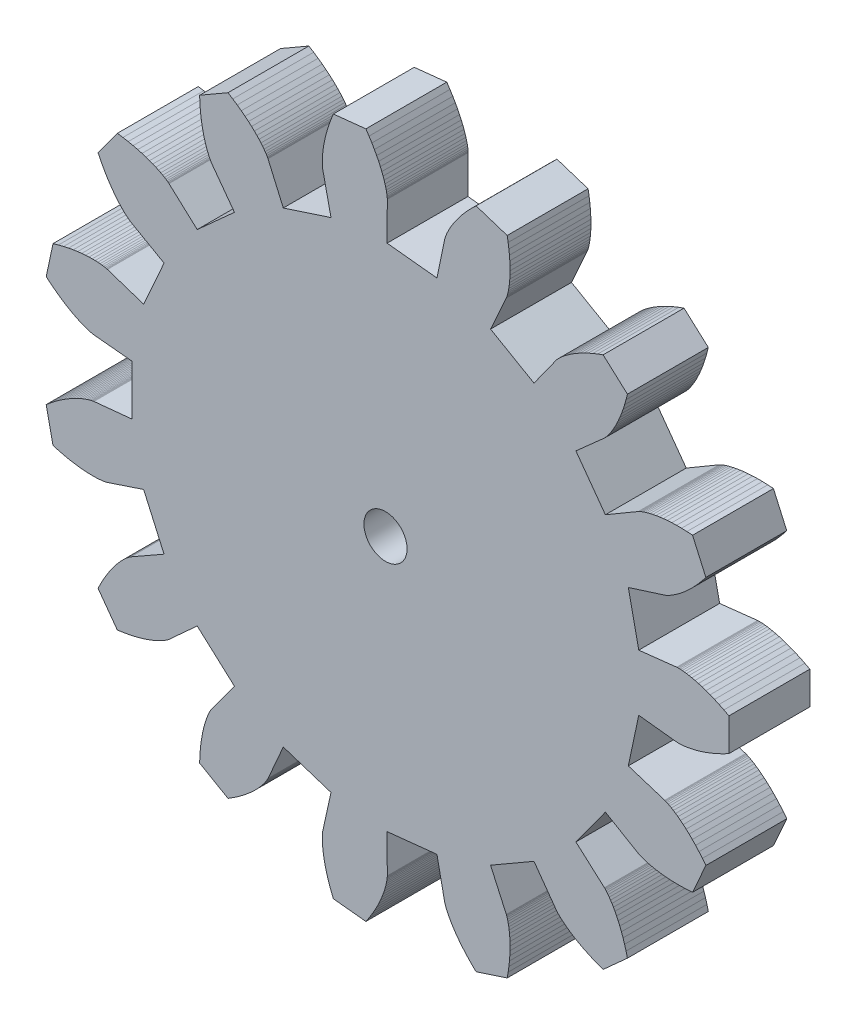
SolidWorks part; units mm, degrees
material "Acrylic (Medium-high impact)"
ref_plane "Front Plane" through (0, 0, 0) normal (0, 0, 1) x (1, 0, 0)
ref_plane "Top Plane" through (0, 0, 0) normal (0, 1, 0) x (1, 0, 0)
ref_plane "Right Plane" through (0, 0, 0) normal (1, 0, 0) x (0, 0, -1)
sketch "Model" plane through (0, 0, 0) normal (0, 0, 1) x (1, 0, 0)
  line L0 (18.784, 2.0911) -> (21.5999, 2.4046)
  line L1 (21.5999, 2.4046) -> (21.6112, 2.4056)
  line L2 (21.6112, 2.4056) -> (21.6451, 2.4077)
  line L3 (21.6451, 2.4077) -> (21.7018, 2.4093)
  line L4 (21.7018, 2.4093) -> (21.7812, 2.4091)
  line L5 (21.7812, 2.4091) -> (21.8831, 2.4055)
  line L6 (21.8831, 2.4055) -> (22.0076, 2.3971)
  line L7 (22.0076, 2.3971) -> (22.1542, 2.3825)
  line L8 (22.1542, 2.3825) -> (22.3228, 2.3602)
  line L9 (22.3228, 2.3602) -> (22.513, 2.3287)
  line L10 (22.513, 2.3287) -> (22.7243, 2.2867)
  line L11 (22.7243, 2.2867) -> (22.9562, 2.2327)
  line L12 (22.9562, 2.2327) -> (23.2081, 2.1655)
  line L13 (23.2081, 2.1655) -> (23.4794, 2.0836)
  line L14 (23.4794, 2.0836) -> (23.7695, 1.9857)
  line L15 (23.7695, 1.9857) -> (24.0775, 1.8706)
  line L16 (24.0775, 1.8706) -> (24.4026, 1.737)
  line L17 (24.4026, 1.737) -> (24.7438, 1.5837)
  line L18 (24.7438, 1.5837) -> (25.1004, 1.4094)
  line L19 (25.1004, 1.4094) -> (25.4711, 1.2132)
  line L20 (25.4711, 1.2132) -> (25.4711, -1.2132)
  line L21 (25.4711, -1.2132) -> (25.1004, -1.4094)
  line L22 (25.1004, -1.4094) -> (24.7438, -1.5837)
  line L23 (24.7438, -1.5837) -> (24.4026, -1.737)
  line L24 (24.4026, -1.737) -> (24.0775, -1.8706)
  line L25 (24.0775, -1.8706) -> (23.7695, -1.9857)
  line L26 (23.7695, -1.9857) -> (23.4794, -2.0836)
  line L27 (23.4794, -2.0836) -> (23.2081, -2.1655)
  line L28 (23.2081, -2.1655) -> (22.9562, -2.2327)
  line L29 (22.9562, -2.2327) -> (22.7243, -2.2867)
  line L30 (22.7243, -2.2867) -> (22.513, -2.3287)
  line L31 (22.513, -2.3287) -> (22.3228, -2.3602)
  line L32 (22.3228, -2.3602) -> (22.1542, -2.3825)
  line L33 (22.1542, -2.3825) -> (22.0076, -2.3971)
  line L34 (22.0076, -2.3971) -> (21.8831, -2.4055)
  line L35 (21.8831, -2.4055) -> (21.7812, -2.4091)
  line L36 (21.7812, -2.4091) -> (21.7018, -2.4093)
  line L37 (21.7018, -2.4093) -> (21.6451, -2.4077)
  line L38 (21.6451, -2.4077) -> (21.6112, -2.4056)
  line L39 (21.6112, -2.4056) -> (21.5999, -2.4046)
  line L40 (21.5999, -2.4046) -> (18.784, -2.0911)
  line L41 (18.784, -2.0911) -> (18.0105, -5.7298)
  line L42 (18.0105, -5.7298) -> (20.7105, -6.5887)
  line L43 (20.7105, -6.5887) -> (20.7213, -6.5924)
  line L44 (20.7213, -6.5924) -> (20.7531, -6.6043)
  line L45 (20.7531, -6.6043) -> (20.8056, -6.6259)
  line L46 (20.8056, -6.6259) -> (20.878, -6.6584)
  line L47 (20.878, -6.6584) -> (20.9697, -6.7031)
  line L48 (20.9697, -6.7031) -> (21.0799, -6.7614)
  line L49 (21.0799, -6.7614) -> (21.2079, -6.8344)
  line L50 (21.2079, -6.8344) -> (21.3529, -6.9234)
  line L51 (21.3529, -6.9234) -> (21.5138, -7.0295)
  line L52 (21.5138, -7.0295) -> (21.6897, -7.1538)
  line L53 (21.6897, -7.1538) -> (21.8796, -7.2974)
  line L54 (21.8796, -7.2974) -> (22.0824, -7.4613)
  line L55 (22.0824, -7.4613) -> (22.297, -7.6465)
  line L56 (22.297, -7.6465) -> (22.5222, -7.8539)
  line L57 (22.5222, -7.8539) -> (22.7567, -8.0843)
  line L58 (22.7567, -8.0843) -> (22.9993, -8.3386)
  line L59 (22.9993, -8.3386) -> (23.2488, -8.6175)
  line L60 (23.2488, -8.6175) -> (23.5036, -8.9216)
  line L61 (23.5036, -8.9216) -> (23.7625, -9.2517)
  line L62 (23.7625, -9.2517) -> (22.7756, -11.4683)
  line L63 (22.7756, -11.4683) -> (22.357, -11.4968)
  line L64 (22.357, -11.4968) -> (21.9605, -11.511)
  line L65 (21.9605, -11.511) -> (21.5863, -11.5123)
  line L66 (21.5863, -11.5123) -> (21.235, -11.5021)
  line L67 (21.235, -11.5021) -> (20.9068, -11.482)
  line L68 (20.9068, -11.482) -> (20.6021, -11.4534)
  line L69 (20.6021, -11.4534) -> (20.3209, -11.4179)
  line L70 (20.3209, -11.4179) -> (20.0633, -11.3768)
  line L71 (20.0633, -11.3768) -> (19.8296, -11.3318)
  line L72 (19.8296, -11.3318) -> (19.6195, -11.2842)
  line L73 (19.6195, -11.2842) -> (19.4329, -11.2356)
  line L74 (19.4329, -11.2356) -> (19.2698, -11.1875)
  line L75 (19.2698, -11.1875) -> (19.1299, -11.1412)
  line L76 (19.1299, -11.1412) -> (19.0128, -11.0982)
  line L77 (19.0128, -11.0982) -> (18.9182, -11.06)
  line L78 (18.9182, -11.06) -> (18.8456, -11.028)
  line L79 (18.8456, -11.028) -> (18.7945, -11.0034)
  line L80 (18.7945, -11.0034) -> (18.7643, -10.9877)
  line L81 (18.7643, -10.9877) -> (18.7544, -10.9822)
  line L82 (18.7544, -10.9822) -> (16.3095, -9.5505)
  line L83 (16.3095, -9.5505) -> (14.1229, -12.56)
  line L84 (14.1229, -12.56) -> (16.2401, -14.4428)
  line L85 (16.2401, -14.4428) -> (16.2484, -14.4506)
  line L86 (16.2484, -14.4506) -> (16.2727, -14.4744)
  line L87 (16.2727, -14.4744) -> (16.3118, -14.5154)
  line L88 (16.3118, -14.5154) -> (16.3648, -14.5745)
  line L89 (16.3648, -14.5745) -> (16.4303, -14.6527)
  line L90 (16.4303, -14.6527) -> (16.5074, -14.7508)
  line L91 (16.5074, -14.7508) -> (16.5946, -14.8696)
  line L92 (16.5946, -14.8696) -> (16.6908, -15.0098)
  line L93 (16.6908, -15.0098) -> (16.7947, -15.1722)
  line L94 (16.7947, -15.1722) -> (16.9048, -15.3573)
  line L95 (16.9048, -15.3573) -> (17.0199, -15.5657)
  line L96 (17.0199, -15.5657) -> (17.1385, -15.798)
  line L97 (17.1385, -15.798) -> (17.2592, -16.0544)
  line L98 (17.2592, -16.0544) -> (17.3806, -16.3355)
  line L99 (17.3806, -16.3355) -> (17.5011, -16.6414)
  line L100 (17.5011, -16.6414) -> (17.6193, -16.9723)
  line L101 (17.6193, -16.9723) -> (17.7338, -17.3286)
  line L102 (17.7338, -17.3286) -> (17.8428, -17.7101)
  line L103 (17.8428, -17.7101) -> (17.9451, -18.1169)
  line L104 (17.9451, -18.1169) -> (16.1419, -19.7405)
  line L105 (16.1419, -19.7405) -> (15.748, -19.5963)
  line L106 (15.748, -19.5963) -> (15.38, -19.4479)
  line L107 (15.38, -19.4479) -> (15.0376, -19.2969)
  line L108 (15.0376, -19.2969) -> (14.7208, -19.1447)
  line L109 (14.7208, -19.1447) -> (14.4292, -18.9929)
  line L110 (14.4292, -18.9929) -> (14.1624, -18.8428)
  line L111 (14.1624, -18.8428) -> (13.92, -18.696)
  line L112 (13.92, -18.696) -> (13.7014, -18.5537)
  line L113 (13.7014, -18.5537) -> (13.5062, -18.4175)
  line L114 (13.5062, -18.4175) -> (13.3336, -18.2886)
  line L115 (13.3336, -18.2886) -> (13.1829, -18.1683)
  line L116 (13.1829, -18.1683) -> (13.0535, -18.058)
  line L117 (13.0535, -18.058) -> (12.9445, -17.9588)
  line L118 (12.9445, -17.9588) -> (12.855, -17.872)
  line L119 (12.855, -17.872) -> (12.7841, -17.7986)
  line L120 (12.7841, -17.7986) -> (12.7308, -17.7397)
  line L121 (12.7308, -17.7397) -> (12.6942, -17.6965)
  line L122 (12.6942, -17.6965) -> (12.673, -17.6699)
  line L123 (12.673, -17.6699) -> (12.6662, -17.6609)
  line L124 (12.6662, -17.6609) -> (11.0149, -15.3584)
  line L125 (11.0149, -15.3584) -> (7.7934, -17.2184)
  line L126 (7.7934, -17.2184) -> (8.9617, -19.7996)
  line L127 (8.9617, -19.7996) -> (8.9661, -19.8101)
  line L128 (8.9661, -19.8101) -> (8.9786, -19.8417)
  line L129 (8.9786, -19.8417) -> (8.9976, -19.8951)
  line L130 (8.9976, -19.8951) -> (9.022, -19.9707)
  line L131 (9.022, -19.9707) -> (9.0501, -20.0688)
  line L132 (9.0501, -20.0688) -> (9.0805, -20.1897)
  line L133 (9.0805, -20.1897) -> (9.1119, -20.3337)
  line L134 (9.1119, -20.3337) -> (9.1428, -20.5009)
  line L135 (9.1428, -20.5009) -> (9.1716, -20.6915)
  line L136 (9.1716, -20.6915) -> (9.1969, -20.9054)
  line L137 (9.1969, -20.9054) -> (9.2173, -21.1426)
  line L138 (9.2173, -21.1426) -> (9.2312, -21.403)
  line L139 (9.2312, -21.403) -> (9.2372, -21.6864)
  line L140 (9.2372, -21.6864) -> (9.2337, -21.9925)
  line L141 (9.2337, -21.9925) -> (9.2194, -22.321)
  line L142 (9.2194, -22.321) -> (9.1928, -22.6714)
  line L143 (9.1928, -22.6714) -> (9.1524, -23.0434)
  line L144 (9.1524, -23.0434) -> (9.0969, -23.4363)
  line L145 (9.0969, -23.4363) -> (9.0248, -23.8496)
  line L146 (9.0248, -23.8496) -> (6.7172, -24.5994)
  line L147 (6.7172, -24.5994) -> (6.416, -24.3074)
  line L148 (6.416, -24.3074) -> (6.1401, -24.0222)
  line L149 (6.1401, -24.0222) -> (5.8888, -23.745)
  line L150 (5.8888, -23.745) -> (5.6613, -23.4771)
  line L151 (5.6613, -23.4771) -> (5.4566, -23.2198)
  line L152 (5.4566, -23.2198) -> (5.2739, -22.9741)
  line L153 (5.2739, -22.9741) -> (5.1122, -22.7414)
  line L154 (5.1122, -22.7414) -> (4.9704, -22.5226)
  line L155 (4.9704, -22.5226) -> (4.8474, -22.3187)
  line L156 (4.8474, -22.3187) -> (4.7422, -22.1307)
  line L157 (4.7422, -22.1307) -> (4.6535, -21.9596)
  line L158 (4.6535, -21.9596) -> (4.5801, -21.8062)
  line L159 (4.5801, -21.8062) -> (4.5209, -21.6712)
  line L160 (4.5209, -21.6712) -> (4.4745, -21.5555)
  line L161 (4.4745, -21.5555) -> (4.4395, -21.4596)
  line L162 (4.4395, -21.4596) -> (4.4148, -21.3842)
  line L163 (4.4148, -21.3842) -> (4.3989, -21.3298)
  line L164 (4.3989, -21.3298) -> (4.3903, -21.2968)
  line L165 (4.3903, -21.2968) -> (4.3878, -21.2858)
  line L166 (4.3878, -21.2858) -> (3.8158, -18.5108)
  line L167 (3.8158, -18.5108) -> (0.1162, -18.8996)
  line L168 (0.1162, -18.8996) -> (0.1337, -21.7329)
  line L169 (0.1337, -21.7329) -> (0.1335, -21.7443)
  line L170 (0.1335, -21.7443) -> (0.132, -21.7782)
  line L171 (0.132, -21.7782) -> (0.1277, -21.8348)
  line L172 (0.1277, -21.8348) -> (0.1192, -21.9137)
  line L173 (0.1192, -21.9137) -> (0.1049, -22.0147)
  line L174 (0.1049, -22.0147) -> (0.0836, -22.1376)
  line L175 (0.0836, -22.1376) -> (0.0537, -22.2819)
  line L176 (0.0537, -22.2819) -> (0.0139, -22.4472)
  line L177 (0.0139, -22.4472) -> (-0.0373, -22.6331)
  line L178 (-0.0373, -22.6331) -> (-0.1012, -22.8388)
  line L179 (-0.1012, -22.8388) -> (-0.1791, -23.0638)
  line L180 (-0.1791, -23.0638) -> (-0.2723, -23.3073)
  line L181 (-0.2723, -23.3073) -> (-0.3821, -23.5686)
  line L182 (-0.3821, -23.5686) -> (-0.5097, -23.8469)
  line L183 (-0.5097, -23.8469) -> (-0.6564, -24.1411)
  line L184 (-0.6564, -24.1411) -> (-0.8233, -24.4504)
  line L185 (-0.8233, -24.4504) -> (-1.0114, -24.7738)
  line L186 (-1.0114, -24.7738) -> (-1.222, -25.1102)
  line L187 (-1.222, -25.1102) -> (-1.4559, -25.4584)
  line L188 (-1.4559, -25.4584) -> (-3.869, -25.2048)
  line L189 (-3.869, -25.2048) -> (-4.0254, -24.8155)
  line L190 (-4.0254, -24.8155) -> (-4.1614, -24.4427)
  line L191 (-4.1614, -24.4427) -> (-4.2783, -24.0873)
  line L192 (-4.2783, -24.0873) -> (-4.3772, -23.75)
  line L193 (-4.3772, -23.75) -> (-4.4594, -23.4317)
  line L194 (-4.4594, -23.4317) -> (-4.5265, -23.133)
  line L195 (-4.5265, -23.133) -> (-4.5795, -22.8546)
  line L196 (-4.5795, -22.8546) -> (-4.6201, -22.597)
  line L197 (-4.6201, -22.597) -> (-4.6495, -22.3607)
  line L198 (-4.6495, -22.3607) -> (-4.6692, -22.1462)
  line L199 (-4.6692, -22.1462) -> (-4.6806, -21.9538)
  line L200 (-4.6806, -21.9538) -> (-4.6852, -21.7838)
  line L201 (-4.6852, -21.7838) -> (-4.6844, -21.6364)
  line L202 (-4.6844, -21.6364) -> (-4.6798, -21.5118)
  line L203 (-4.6798, -21.5118) -> (-4.6727, -21.41)
  line L204 (-4.6727, -21.41) -> (-4.6646, -21.3311)
  line L205 (-4.6646, -21.3311) -> (-4.657, -21.2749)
  line L206 (-4.657, -21.2749) -> (-4.6514, -21.2413)
  line L207 (-4.6514, -21.2413) -> (-4.6493, -21.2302)
  line L208 (-4.6493, -21.2302) -> (-4.0431, -18.4625)
  line L209 (-4.0431, -18.4625) -> (-7.581, -17.313)
  line L210 (-7.581, -17.313) -> (-8.7175, -19.9084)
  line L211 (-8.7175, -19.9084) -> (-8.7222, -19.9187)
  line L212 (-8.7222, -19.9187) -> (-8.7374, -19.9491)
  line L213 (-8.7374, -19.9491) -> (-8.7643, -19.999)
  line L214 (-8.7643, -19.999) -> (-8.8042, -20.0676)
  line L215 (-8.8042, -20.0676) -> (-8.8583, -20.1541)
  line L216 (-8.8583, -20.1541) -> (-8.9278, -20.2577)
  line L217 (-8.9278, -20.2577) -> (-9.0138, -20.3774)
  line L218 (-9.0138, -20.3774) -> (-9.1174, -20.5122)
  line L219 (-9.1174, -20.5122) -> (-9.2398, -20.6612)
  line L220 (-9.2398, -20.6612) -> (-9.3818, -20.8231)
  line L221 (-9.3818, -20.8231) -> (-9.5445, -20.997)
  line L222 (-9.5445, -20.997) -> (-9.7287, -21.1815)
  line L223 (-9.7287, -21.1815) -> (-9.9353, -21.3756)
  line L224 (-9.9353, -21.3756) -> (-10.165, -21.5779)
  line L225 (-10.165, -21.5779) -> (-10.4187, -21.787)
  line L226 (-10.4187, -21.787) -> (-10.697, -22.0017)
  line L227 (-10.697, -22.0017) -> (-11.0004, -22.2206)
  line L228 (-11.0004, -22.2206) -> (-11.3296, -22.4423)
  line L229 (-11.3296, -22.4423) -> (-11.6849, -22.6652)
  line L230 (-11.6849, -22.6652) -> (-13.7862, -21.452)
  line L231 (-13.7862, -21.452) -> (-13.7708, -21.0328)
  line L232 (-13.7708, -21.0328) -> (-13.7434, -20.6369)
  line L233 (-13.7434, -20.6369) -> (-13.7056, -20.2647)
  line L234 (-13.7056, -20.2647) -> (-13.6587, -19.9164)
  line L235 (-13.6587, -19.9164) -> (-13.6044, -19.5921)
  line L236 (-13.6044, -19.5921) -> (-13.5442, -19.292)
  line L237 (-13.5442, -19.292) -> (-13.4794, -19.0161)
  line L238 (-13.4794, -19.0161) -> (-13.4117, -18.7642)
  line L239 (-13.4117, -18.7642) -> (-13.3425, -18.5364)
  line L240 (-13.3425, -18.5364) -> (-13.2732, -18.3325)
  line L241 (-13.2732, -18.3325) -> (-13.2054, -18.152)
  line L242 (-13.2054, -18.152) -> (-13.1404, -17.9949)
  line L243 (-13.1404, -17.9949) -> (-13.0798, -17.8605)
  line L244 (-13.0798, -17.8605) -> (-13.0248, -17.7486)
  line L245 (-13.0248, -17.7486) -> (-12.9769, -17.6585)
  line L246 (-12.9769, -17.6585) -> (-12.9375, -17.5896)
  line L247 (-12.9375, -17.5896) -> (-12.9077, -17.5414)
  line L248 (-12.9077, -17.5414) -> (-12.8889, -17.513)
  line L249 (-12.8889, -17.513) -> (-12.8824, -17.5037)
  line L250 (-12.8824, -17.5037) -> (-11.203, -15.2218)
  line L251 (-11.203, -15.2218) -> (-13.9674, -12.7327)
  line L252 (-13.9674, -12.7327) -> (-16.0613, -14.6415)
  line L253 (-16.0613, -14.6415) -> (-16.0698, -14.6489)
  line L254 (-16.0698, -14.6489) -> (-16.0961, -14.6706)
  line L255 (-16.0961, -14.6706) -> (-16.1409, -14.7052)
  line L256 (-16.1409, -14.7052) -> (-16.2053, -14.7517)
  line L257 (-16.2053, -14.7517) -> (-16.2899, -14.8087)
  line L258 (-16.2899, -14.8087) -> (-16.3955, -14.8751)
  line L259 (-16.3955, -14.8751) -> (-16.5227, -14.9494)
  line L260 (-16.5227, -14.9494) -> (-16.6723, -15.0304)
  line L261 (-16.6723, -15.0304) -> (-16.8446, -15.1167)
  line L262 (-16.8446, -15.1167) -> (-17.0402, -15.2069)
  line L263 (-17.0402, -15.2069) -> (-17.2595, -15.2996)
  line L264 (-17.2595, -15.2996) -> (-17.5029, -15.3933)
  line L265 (-17.5029, -15.3933) -> (-17.7706, -15.4865)
  line L266 (-17.7706, -15.4865) -> (-18.0627, -15.5779)
  line L267 (-18.0627, -15.5779) -> (-18.3796, -15.6658)
  line L268 (-18.3796, -15.6658) -> (-18.7211, -15.7487)
  line L269 (-18.7211, -15.7487) -> (-19.0873, -15.8253)
  line L270 (-19.0873, -15.8253) -> (-19.4782, -15.8939)
  line L271 (-19.4782, -15.8939) -> (-19.8935, -15.953)
  line L272 (-19.8935, -15.953) -> (-21.3196, -13.99)
  line L273 (-21.3196, -13.99) -> (-21.1351, -13.6133)
  line L274 (-21.1351, -13.6133) -> (-20.949, -13.2628)
  line L275 (-20.949, -13.2628) -> (-20.7631, -12.9382)
  line L276 (-20.7631, -12.9382) -> (-20.5786, -12.639)
  line L277 (-20.5786, -12.639) -> (-20.3971, -12.3649)
  line L278 (-20.3971, -12.3649) -> (-20.22, -12.1152)
  line L279 (-20.22, -12.1152) -> (-20.0486, -11.8895)
  line L280 (-20.0486, -11.8895) -> (-19.8843, -11.687)
  line L281 (-19.8843, -11.687) -> (-19.7284, -11.507)
  line L282 (-19.7284, -11.507) -> (-19.5822, -11.3488)
  line L283 (-19.5822, -11.3488) -> (-19.4468, -11.2116)
  line L284 (-19.4468, -11.2116) -> (-19.3236, -11.0944)
  line L285 (-19.3236, -11.0944) -> (-19.2135, -10.9964)
  line L286 (-19.2135, -10.9964) -> (-19.1178, -10.9165)
  line L287 (-19.1178, -10.9165) -> (-19.0374, -10.8536)
  line L288 (-19.0374, -10.8536) -> (-18.9733, -10.8068)
  line L289 (-18.9733, -10.8068) -> (-18.9265, -10.7748)
  line L290 (-18.9265, -10.7748) -> (-18.8978, -10.7565)
  line L291 (-18.8978, -10.7565) -> (-18.8881, -10.7507)
  line L292 (-18.8881, -10.7507) -> (-16.4257, -9.3492)
  line L293 (-16.4257, -9.3492) -> (-17.9387, -5.9508)
  line L294 (-17.9387, -5.9508) -> (-20.6279, -6.843)
  line L295 (-20.6279, -6.843) -> (-20.6388, -6.8463)
  line L296 (-20.6388, -6.8463) -> (-20.6716, -6.8554)
  line L297 (-20.6716, -6.8554) -> (-20.7266, -6.8688)
  line L298 (-20.7266, -6.8688) -> (-20.8043, -6.885)
  line L299 (-20.8043, -6.885) -> (-20.9048, -6.9027)
  line L300 (-20.9048, -6.9027) -> (-21.0283, -6.9204)
  line L301 (-21.0283, -6.9204) -> (-21.1748, -6.9366)
  line L302 (-21.1748, -6.9366) -> (-21.3443, -6.9498)
  line L303 (-21.3443, -6.9498) -> (-21.5368, -6.9585)
  line L304 (-21.5368, -6.9585) -> (-21.7522, -6.9614)
  line L305 (-21.7522, -6.9614) -> (-21.9903, -6.9568)
  line L306 (-21.9903, -6.9568) -> (-22.2507, -6.9434)
  line L307 (-22.2507, -6.9434) -> (-22.5332, -6.9197)
  line L308 (-22.5332, -6.9197) -> (-22.8372, -6.8843)
  line L309 (-22.8372, -6.8843) -> (-23.1624, -6.8357)
  line L310 (-23.1624, -6.8357) -> (-23.5082, -6.7726)
  line L311 (-23.5082, -6.7726) -> (-23.8739, -6.6936)
  line L312 (-23.8739, -6.6936) -> (-24.2588, -6.5973)
  line L313 (-24.2588, -6.5973) -> (-24.6623, -6.4824)
  line L314 (-24.6623, -6.4824) -> (-25.1667, -4.1091)
  line L315 (-25.1667, -4.1091) -> (-24.8449, -3.84)
  line L316 (-24.8449, -3.84) -> (-24.5324, -3.5955)
  line L317 (-24.5324, -3.5955) -> (-24.2304, -3.3745)
  line L318 (-24.2304, -3.3745) -> (-23.9403, -3.1762)
  line L319 (-23.9403, -3.1762) -> (-23.6629, -2.9996)
  line L320 (-23.6629, -2.9996) -> (-23.3996, -2.8436)
  line L321 (-23.3996, -2.8436) -> (-23.1512, -2.7071)
  line L322 (-23.1512, -2.7071) -> (-22.9187, -2.5889)
  line L323 (-22.9187, -2.5889) -> (-22.7031, -2.4879)
  line L324 (-22.7031, -2.4879) -> (-22.5052, -2.4029)
  line L325 (-22.5052, -2.4029) -> (-22.3257, -2.3326)
  line L326 (-22.3257, -2.3326) -> (-22.1655, -2.2757)
  line L327 (-22.1655, -2.2757) -> (-22.025, -2.2309)
  line L328 (-22.025, -2.2309) -> (-21.9051, -2.1968)
  line L329 (-21.9051, -2.1968) -> (-21.8061, -2.1721)
  line L330 (-21.8061, -2.1721) -> (-21.7285, -2.1554)
  line L331 (-21.7285, -2.1554) -> (-21.6727, -2.1452)
  line L332 (-21.6727, -2.1452) -> (-21.6391, -2.1401)
  line L333 (-21.6391, -2.1401) -> (-21.6278, -2.1388)
  line L334 (-21.6278, -2.1388) -> (-18.8083, -1.86)
  line L335 (-18.8083, -1.86) -> (-18.8083, 1.86)
  line L336 (-18.8083, 1.86) -> (-21.6278, 2.1388)
  line L337 (-21.6278, 2.1388) -> (-21.6391, 2.1401)
  line L338 (-21.6391, 2.1401) -> (-21.6727, 2.1452)
  line L339 (-21.6727, 2.1452) -> (-21.7285, 2.1554)
  line L340 (-21.7285, 2.1554) -> (-21.8061, 2.1721)
  line L341 (-21.8061, 2.1721) -> (-21.9051, 2.1968)
  line L342 (-21.9051, 2.1968) -> (-22.025, 2.2309)
  line L343 (-22.025, 2.2309) -> (-22.1655, 2.2757)
  line L344 (-22.1655, 2.2757) -> (-22.3257, 2.3326)
  line L345 (-22.3257, 2.3326) -> (-22.5052, 2.4029)
  line L346 (-22.5052, 2.4029) -> (-22.7031, 2.4879)
  line L347 (-22.7031, 2.4879) -> (-22.9187, 2.5889)
  line L348 (-22.9187, 2.5889) -> (-23.1512, 2.7071)
  line L349 (-23.1512, 2.7071) -> (-23.3996, 2.8436)
  line L350 (-23.3996, 2.8436) -> (-23.6629, 2.9996)
  line L351 (-23.6629, 2.9996) -> (-23.9403, 3.1762)
  line L352 (-23.9403, 3.1762) -> (-24.2304, 3.3745)
  line L353 (-24.2304, 3.3745) -> (-24.5324, 3.5955)
  line L354 (-24.5324, 3.5955) -> (-24.8449, 3.84)
  line L355 (-24.8449, 3.84) -> (-25.1667, 4.1091)
  line L356 (-25.1667, 4.1091) -> (-24.6623, 6.4824)
  line L357 (-24.6623, 6.4824) -> (-24.2588, 6.5973)
  line L358 (-24.2588, 6.5973) -> (-23.8739, 6.6936)
  line L359 (-23.8739, 6.6936) -> (-23.5082, 6.7726)
  line L360 (-23.5082, 6.7726) -> (-23.1624, 6.8357)
  line L361 (-23.1624, 6.8357) -> (-22.8372, 6.8843)
  line L362 (-22.8372, 6.8843) -> (-22.5332, 6.9197)
  line L363 (-22.5332, 6.9197) -> (-22.2507, 6.9434)
  line L364 (-22.2507, 6.9434) -> (-21.9903, 6.9568)
  line L365 (-21.9903, 6.9568) -> (-21.7522, 6.9614)
  line L366 (-21.7522, 6.9614) -> (-21.5368, 6.9585)
  line L367 (-21.5368, 6.9585) -> (-21.3443, 6.9498)
  line L368 (-21.3443, 6.9498) -> (-21.1748, 6.9366)
  line L369 (-21.1748, 6.9366) -> (-21.0283, 6.9204)
  line L370 (-21.0283, 6.9204) -> (-20.9048, 6.9027)
  line L371 (-20.9048, 6.9027) -> (-20.8043, 6.885)
  line L372 (-20.8043, 6.885) -> (-20.7266, 6.8688)
  line L373 (-20.7266, 6.8688) -> (-20.6716, 6.8554)
  line L374 (-20.6716, 6.8554) -> (-20.6388, 6.8463)
  line L375 (-20.6388, 6.8463) -> (-20.6279, 6.843)
  line L376 (-20.6279, 6.843) -> (-17.9387, 5.9508)
  line L377 (-17.9387, 5.9508) -> (-16.4257, 9.3492)
  line L378 (-16.4257, 9.3492) -> (-18.8881, 10.7507)
  line L379 (-18.8881, 10.7507) -> (-18.8978, 10.7565)
  line L380 (-18.8978, 10.7565) -> (-18.9265, 10.7748)
  line L381 (-18.9265, 10.7748) -> (-18.9733, 10.8068)
  line L382 (-18.9733, 10.8068) -> (-19.0374, 10.8536)
  line L383 (-19.0374, 10.8536) -> (-19.1178, 10.9165)
  line L384 (-19.1178, 10.9165) -> (-19.2135, 10.9964)
  line L385 (-19.2135, 10.9964) -> (-19.3236, 11.0944)
  line L386 (-19.3236, 11.0944) -> (-19.4468, 11.2116)
  line L387 (-19.4468, 11.2116) -> (-19.5822, 11.3488)
  line L388 (-19.5822, 11.3488) -> (-19.7284, 11.507)
  line L389 (-19.7284, 11.507) -> (-19.8843, 11.687)
  line L390 (-19.8843, 11.687) -> (-20.0486, 11.8895)
  line L391 (-20.0486, 11.8895) -> (-20.22, 12.1152)
  line L392 (-20.22, 12.1152) -> (-20.3971, 12.3649)
  line L393 (-20.3971, 12.3649) -> (-20.5786, 12.639)
  line L394 (-20.5786, 12.639) -> (-20.7631, 12.9382)
  line L395 (-20.7631, 12.9382) -> (-20.949, 13.2628)
  line L396 (-20.949, 13.2628) -> (-21.1351, 13.6133)
  line L397 (-21.1351, 13.6133) -> (-21.3196, 13.99)
  line L398 (-21.3196, 13.99) -> (-19.8935, 15.953)
  line L399 (-19.8935, 15.953) -> (-19.4782, 15.8939)
  line L400 (-19.4782, 15.8939) -> (-19.0873, 15.8253)
  line L401 (-19.0873, 15.8253) -> (-18.7211, 15.7487)
  line L402 (-18.7211, 15.7487) -> (-18.3796, 15.6658)
  line L403 (-18.3796, 15.6658) -> (-18.0627, 15.5779)
  line L404 (-18.0627, 15.5779) -> (-17.7706, 15.4865)
  line L405 (-17.7706, 15.4865) -> (-17.5029, 15.3933)
  line L406 (-17.5029, 15.3933) -> (-17.2595, 15.2996)
  line L407 (-17.2595, 15.2996) -> (-17.0402, 15.2069)
  line L408 (-17.0402, 15.2069) -> (-16.8446, 15.1167)
  line L409 (-16.8446, 15.1167) -> (-16.6723, 15.0304)
  line L410 (-16.6723, 15.0304) -> (-16.5227, 14.9494)
  line L411 (-16.5227, 14.9494) -> (-16.3955, 14.8751)
  line L412 (-16.3955, 14.8751) -> (-16.2899, 14.8087)
  line L413 (-16.2899, 14.8087) -> (-16.2053, 14.7517)
  line L414 (-16.2053, 14.7517) -> (-16.1409, 14.7052)
  line L415 (-16.1409, 14.7052) -> (-16.0961, 14.6706)
  line L416 (-16.0961, 14.6706) -> (-16.0698, 14.6489)
  line L417 (-16.0698, 14.6489) -> (-16.0613, 14.6415)
  line L418 (-16.0613, 14.6415) -> (-13.9674, 12.7327)
  line L419 (-13.9674, 12.7327) -> (-11.203, 15.2218)
  line L420 (-11.203, 15.2218) -> (-12.8824, 17.5037)
  line L421 (-12.8824, 17.5037) -> (-12.8889, 17.513)
  line L422 (-12.8889, 17.513) -> (-12.9077, 17.5414)
  line L423 (-12.9077, 17.5414) -> (-12.9375, 17.5896)
  line L424 (-12.9375, 17.5896) -> (-12.9769, 17.6585)
  line L425 (-12.9769, 17.6585) -> (-13.0248, 17.7486)
  line L426 (-13.0248, 17.7486) -> (-13.0798, 17.8605)
  line L427 (-13.0798, 17.8605) -> (-13.1404, 17.9949)
  line L428 (-13.1404, 17.9949) -> (-13.2054, 18.152)
  line L429 (-13.2054, 18.152) -> (-13.2732, 18.3325)
  line L430 (-13.2732, 18.3325) -> (-13.3425, 18.5364)
  line L431 (-13.3425, 18.5364) -> (-13.4117, 18.7642)
  line L432 (-13.4117, 18.7642) -> (-13.4794, 19.0161)
  line L433 (-13.4794, 19.0161) -> (-13.5442, 19.292)
  line L434 (-13.5442, 19.292) -> (-13.6044, 19.5921)
  line L435 (-13.6044, 19.5921) -> (-13.6587, 19.9164)
  line L436 (-13.6587, 19.9164) -> (-13.7056, 20.2647)
  line L437 (-13.7056, 20.2647) -> (-13.7434, 20.6369)
  line L438 (-13.7434, 20.6369) -> (-13.7708, 21.0328)
  line L439 (-13.7708, 21.0328) -> (-13.7862, 21.452)
  line L440 (-13.7862, 21.452) -> (-11.6849, 22.6652)
  line L441 (-11.6849, 22.6652) -> (-11.3296, 22.4423)
  line L442 (-11.3296, 22.4423) -> (-11.0004, 22.2206)
  line L443 (-11.0004, 22.2206) -> (-10.697, 22.0017)
  line L444 (-10.697, 22.0017) -> (-10.4187, 21.787)
  line L445 (-10.4187, 21.787) -> (-10.165, 21.5779)
  line L446 (-10.165, 21.5779) -> (-9.9353, 21.3756)
  line L447 (-9.9353, 21.3756) -> (-9.7287, 21.1815)
  line L448 (-9.7287, 21.1815) -> (-9.5445, 20.997)
  line L449 (-9.5445, 20.997) -> (-9.3818, 20.8231)
  line L450 (-9.3818, 20.8231) -> (-9.2398, 20.6612)
  line L451 (-9.2398, 20.6612) -> (-9.1174, 20.5122)
  line L452 (-9.1174, 20.5122) -> (-9.0138, 20.3774)
  line L453 (-9.0138, 20.3774) -> (-8.9278, 20.2577)
  line L454 (-8.9278, 20.2577) -> (-8.8583, 20.1541)
  line L455 (-8.8583, 20.1541) -> (-8.8042, 20.0676)
  line L456 (-8.8042, 20.0676) -> (-8.7643, 19.999)
  line L457 (-8.7643, 19.999) -> (-8.7374, 19.9491)
  line L458 (-8.7374, 19.9491) -> (-8.7222, 19.9187)
  line L459 (-8.7222, 19.9187) -> (-8.7175, 19.9084)
  line L460 (-8.7175, 19.9084) -> (-7.581, 17.313)
  line L461 (-7.581, 17.313) -> (-4.0431, 18.4625)
  line L462 (-4.0431, 18.4625) -> (-4.6493, 21.2302)
  line L463 (-4.6493, 21.2302) -> (-4.6514, 21.2413)
  line L464 (-4.6514, 21.2413) -> (-4.657, 21.2749)
  line L465 (-4.657, 21.2749) -> (-4.6646, 21.3311)
  line L466 (-4.6646, 21.3311) -> (-4.6727, 21.41)
  line L467 (-4.6727, 21.41) -> (-4.6798, 21.5118)
  line L468 (-4.6798, 21.5118) -> (-4.6844, 21.6364)
  line L469 (-4.6844, 21.6364) -> (-4.6852, 21.7838)
  line L470 (-4.6852, 21.7838) -> (-4.6806, 21.9538)
  line L471 (-4.6806, 21.9538) -> (-4.6692, 22.1462)
  line L472 (-4.6692, 22.1462) -> (-4.6495, 22.3607)
  line L473 (-4.6495, 22.3607) -> (-4.6201, 22.597)
  line L474 (-4.6201, 22.597) -> (-4.5795, 22.8546)
  line L475 (-4.5795, 22.8546) -> (-4.5265, 23.133)
  line L476 (-4.5265, 23.133) -> (-4.4594, 23.4317)
  line L477 (-4.4594, 23.4317) -> (-4.3772, 23.75)
  line L478 (-4.3772, 23.75) -> (-4.2783, 24.0873)
  line L479 (-4.2783, 24.0873) -> (-4.1614, 24.4427)
  line L480 (-4.1614, 24.4427) -> (-4.0254, 24.8155)
  line L481 (-4.0254, 24.8155) -> (-3.869, 25.2048)
  line L482 (-3.869, 25.2048) -> (-1.4559, 25.4584)
  line L483 (-1.4559, 25.4584) -> (-1.222, 25.1102)
  line L484 (-1.222, 25.1102) -> (-1.0114, 24.7738)
  line L485 (-1.0114, 24.7738) -> (-0.8233, 24.4504)
  line L486 (-0.8233, 24.4504) -> (-0.6564, 24.1411)
  line L487 (-0.6564, 24.1411) -> (-0.5097, 23.8469)
  line L488 (-0.5097, 23.8469) -> (-0.3821, 23.5686)
  line L489 (-0.3821, 23.5686) -> (-0.2723, 23.3073)
  line L490 (-0.2723, 23.3073) -> (-0.1791, 23.0638)
  line L491 (-0.1791, 23.0638) -> (-0.1012, 22.8388)
  line L492 (-0.1012, 22.8388) -> (-0.0373, 22.6331)
  line L493 (-0.0373, 22.6331) -> (0.0139, 22.4472)
  line L494 (0.0139, 22.4472) -> (0.0537, 22.2819)
  line L495 (0.0537, 22.2819) -> (0.0836, 22.1376)
  line L496 (0.0836, 22.1376) -> (0.1049, 22.0147)
  line L497 (0.1049, 22.0147) -> (0.1192, 21.9137)
  line L498 (0.1192, 21.9137) -> (0.1277, 21.8348)
  line L499 (0.1277, 21.8348) -> (0.132, 21.7782)
  line L500 (0.132, 21.7782) -> (0.1335, 21.7443)
  line L501 (0.1335, 21.7443) -> (0.1337, 21.7329)
  line L502 (0.1337, 21.7329) -> (0.1162, 18.8996)
  line L503 (0.1162, 18.8996) -> (3.8158, 18.5108)
  line L504 (3.8158, 18.5108) -> (4.3878, 21.2858)
  line L505 (4.3878, 21.2858) -> (4.3903, 21.2968)
  line L506 (4.3903, 21.2968) -> (4.3989, 21.3298)
  line L507 (4.3989, 21.3298) -> (4.4148, 21.3842)
  line L508 (4.4148, 21.3842) -> (4.4395, 21.4596)
  line L509 (4.4395, 21.4596) -> (4.4745, 21.5555)
  line L510 (4.4745, 21.5555) -> (4.5209, 21.6712)
  line L511 (4.5209, 21.6712) -> (4.5801, 21.8062)
  line L512 (4.5801, 21.8062) -> (4.6535, 21.9596)
  line L513 (4.6535, 21.9596) -> (4.7422, 22.1307)
  line L514 (4.7422, 22.1307) -> (4.8474, 22.3187)
  line L515 (4.8474, 22.3187) -> (4.9704, 22.5226)
  line L516 (4.9704, 22.5226) -> (5.1122, 22.7414)
  line L517 (5.1122, 22.7414) -> (5.2739, 22.9741)
  line L518 (5.2739, 22.9741) -> (5.4566, 23.2198)
  line L519 (5.4566, 23.2198) -> (5.6613, 23.4771)
  line L520 (5.6613, 23.4771) -> (5.8888, 23.745)
  line L521 (5.8888, 23.745) -> (6.1401, 24.0222)
  line L522 (6.1401, 24.0222) -> (6.416, 24.3074)
  line L523 (6.416, 24.3074) -> (6.7172, 24.5994)
  line L524 (6.7172, 24.5994) -> (9.0248, 23.8496)
  line L525 (9.0248, 23.8496) -> (9.0969, 23.4363)
  line L526 (9.0969, 23.4363) -> (9.1524, 23.0434)
  line L527 (9.1524, 23.0434) -> (9.1928, 22.6714)
  line L528 (9.1928, 22.6714) -> (9.2194, 22.321)
  line L529 (9.2194, 22.321) -> (9.2337, 21.9925)
  line L530 (9.2337, 21.9925) -> (9.2372, 21.6864)
  line L531 (9.2372, 21.6864) -> (9.2312, 21.403)
  line L532 (9.2312, 21.403) -> (9.2173, 21.1426)
  line L533 (9.2173, 21.1426) -> (9.1969, 20.9054)
  line L534 (9.1969, 20.9054) -> (9.1716, 20.6915)
  line L535 (9.1716, 20.6915) -> (9.1428, 20.5009)
  line L536 (9.1428, 20.5009) -> (9.1119, 20.3337)
  line L537 (9.1119, 20.3337) -> (9.0805, 20.1897)
  line L538 (9.0805, 20.1897) -> (9.0501, 20.0688)
  line L539 (9.0501, 20.0688) -> (9.022, 19.9707)
  line L540 (9.022, 19.9707) -> (8.9976, 19.8951)
  line L541 (8.9976, 19.8951) -> (8.9786, 19.8417)
  line L542 (8.9786, 19.8417) -> (8.9661, 19.8101)
  line L543 (8.9661, 19.8101) -> (8.9617, 19.7996)
  line L544 (8.9617, 19.7996) -> (7.7934, 17.2184)
  line L545 (7.7934, 17.2184) -> (11.0149, 15.3584)
  line L546 (11.0149, 15.3584) -> (12.6662, 17.6609)
  line L547 (12.6662, 17.6609) -> (12.673, 17.6699)
  line L548 (12.673, 17.6699) -> (12.6942, 17.6965)
  line L549 (12.6942, 17.6965) -> (12.7308, 17.7397)
  line L550 (12.7308, 17.7397) -> (12.7841, 17.7986)
  line L551 (12.7841, 17.7986) -> (12.855, 17.872)
  line L552 (12.855, 17.872) -> (12.9445, 17.9588)
  line L553 (12.9445, 17.9588) -> (13.0535, 18.058)
  line L554 (13.0535, 18.058) -> (13.1829, 18.1683)
  line L555 (13.1829, 18.1683) -> (13.3336, 18.2886)
  line L556 (13.3336, 18.2886) -> (13.5062, 18.4175)
  line L557 (13.5062, 18.4175) -> (13.7014, 18.5537)
  line L558 (13.7014, 18.5537) -> (13.92, 18.696)
  line L559 (13.92, 18.696) -> (14.1624, 18.8428)
  line L560 (14.1624, 18.8428) -> (14.4292, 18.9929)
  line L561 (14.4292, 18.9929) -> (14.7208, 19.1447)
  line L562 (14.7208, 19.1447) -> (15.0376, 19.2969)
  line L563 (15.0376, 19.2969) -> (15.38, 19.4479)
  line L564 (15.38, 19.4479) -> (15.748, 19.5963)
  line L565 (15.748, 19.5963) -> (16.1419, 19.7405)
  line L566 (16.1419, 19.7405) -> (17.9451, 18.1169)
  line L567 (17.9451, 18.1169) -> (17.8428, 17.7101)
  line L568 (17.8428, 17.7101) -> (17.7338, 17.3286)
  line L569 (17.7338, 17.3286) -> (17.6193, 16.9723)
  line L570 (17.6193, 16.9723) -> (17.5011, 16.6414)
  line L571 (17.5011, 16.6414) -> (17.3806, 16.3355)
  line L572 (17.3806, 16.3355) -> (17.2592, 16.0544)
  line L573 (17.2592, 16.0544) -> (17.1385, 15.798)
  line L574 (17.1385, 15.798) -> (17.0199, 15.5657)
  line L575 (17.0199, 15.5657) -> (16.9048, 15.3573)
  line L576 (16.9048, 15.3573) -> (16.7947, 15.1722)
  line L577 (16.7947, 15.1722) -> (16.6908, 15.0098)
  line L578 (16.6908, 15.0098) -> (16.5946, 14.8696)
  line L579 (16.5946, 14.8696) -> (16.5074, 14.7508)
  line L580 (16.5074, 14.7508) -> (16.4303, 14.6527)
  line L581 (16.4303, 14.6527) -> (16.3648, 14.5745)
  line L582 (16.3648, 14.5745) -> (16.3118, 14.5154)
  line L583 (16.3118, 14.5154) -> (16.2727, 14.4744)
  line L584 (16.2727, 14.4744) -> (16.2484, 14.4506)
  line L585 (16.2484, 14.4506) -> (16.2401, 14.4428)
  line L586 (16.2401, 14.4428) -> (14.1229, 12.56)
  line L587 (14.1229, 12.56) -> (16.3095, 9.5505)
  line L588 (16.3095, 9.5505) -> (18.7544, 10.9822)
  line L589 (18.7544, 10.9822) -> (18.7643, 10.9877)
  line L590 (18.7643, 10.9877) -> (18.7945, 11.0034)
  line L591 (18.7945, 11.0034) -> (18.8456, 11.028)
  line L592 (18.8456, 11.028) -> (18.9182, 11.06)
  line L593 (18.9182, 11.06) -> (19.0128, 11.0982)
  line L594 (19.0128, 11.0982) -> (19.1299, 11.1412)
  line L595 (19.1299, 11.1412) -> (19.2698, 11.1875)
  line L596 (19.2698, 11.1875) -> (19.4329, 11.2356)
  line L597 (19.4329, 11.2356) -> (19.6195, 11.2842)
  line L598 (19.6195, 11.2842) -> (19.8296, 11.3318)
  line L599 (19.8296, 11.3318) -> (20.0633, 11.3768)
  line L600 (20.0633, 11.3768) -> (20.3209, 11.4179)
  line L601 (20.3209, 11.4179) -> (20.6021, 11.4534)
  line L602 (20.6021, 11.4534) -> (20.9068, 11.482)
  line L603 (20.9068, 11.482) -> (21.235, 11.5021)
  line L604 (21.235, 11.5021) -> (21.5863, 11.5123)
  line L605 (21.5863, 11.5123) -> (21.9605, 11.511)
  line L606 (21.9605, 11.511) -> (22.357, 11.4968)
  line L607 (22.357, 11.4968) -> (22.7756, 11.4683)
  line L608 (22.7756, 11.4683) -> (23.7625, 9.2517)
  line L609 (23.7625, 9.2517) -> (23.5036, 8.9216)
  line L610 (23.5036, 8.9216) -> (23.2488, 8.6175)
  line L611 (23.2488, 8.6175) -> (22.9993, 8.3386)
  line L612 (22.9993, 8.3386) -> (22.7567, 8.0843)
  line L613 (22.7567, 8.0843) -> (22.5222, 7.8539)
  line L614 (22.5222, 7.8539) -> (22.297, 7.6465)
  line L615 (22.297, 7.6465) -> (22.0824, 7.4613)
  line L616 (22.0824, 7.4613) -> (21.8796, 7.2974)
  line L617 (21.8796, 7.2974) -> (21.6897, 7.1538)
  line L618 (21.6897, 7.1538) -> (21.5138, 7.0295)
  line L619 (21.5138, 7.0295) -> (21.3529, 6.9234)
  line L620 (21.3529, 6.9234) -> (21.2079, 6.8344)
  line L621 (21.2079, 6.8344) -> (21.0799, 6.7614)
  line L622 (21.0799, 6.7614) -> (20.9697, 6.7031)
  line L623 (20.9697, 6.7031) -> (20.878, 6.6584)
  line L624 (20.878, 6.6584) -> (20.8056, 6.6259)
  line L625 (20.8056, 6.6259) -> (20.7531, 6.6043)
  line L626 (20.7531, 6.6043) -> (20.7213, 6.5924)
  line L627 (20.7213, 6.5924) -> (20.7105, 6.5887)
  line L628 (20.7105, 6.5887) -> (18.0105, 5.7298)
  line L629 (18.0105, 5.7298) -> (18.784, 2.0911)
extrude "Boss-Extrude1" add sketch "Model" along normal blind 6 contours L420 L421 L422 L423 L424 L425 L426 L427 L428 L429 L430 L431 L432 L433 L434 L435 L436 L437 L438 L439 L440 L441 L442 L443 L444 L445 L446 L447 L448 L449 L450 L451 L452 L453 L454 L455 L456 L457 L458 L459 L460 L461 L462 L463 L464 L465 L466 L467 L468 L469 L470 L471 L472 L473 L474 L475 L476 L477 L478 L479 L480 L481 L482 L483 L484 L485 L486 L487 L488 L489 L490 L491 L492 L493 L494 L495 L496 L497 L498 L499 L500 L501 L502 L503 L504 L505 L506 L507 L508 L509 L510 L511 L512 L513 L514 L515 L516 L517 L518 L519 L520 L521 L522 L523 L524 L525 L526 L527 L528 L529 L530 L531 L532 L533 L534 L535 L536 L537 L538 L539 L540 L541 L542 L543 L544 L545 L546 L547 L548 L549 L550 L551 L552 L553 L554 L555 L556 L557 L558 L559 L560 L561 L562 L563 L564 L565 L566 L567 L568 L569 L570 L571 L572 L573 L574 L575 L576 L577 L578 L579 L580 L581 L582 L583 L584 L585 L586 L587 L588 L589 L590 L591 L592 L593 L594 L595 L596 L597 L598 L599 L600 L601 L602 L603 L604 L605 L606 L607 L608 L609 L610 L611 L612 L613 L614 L615 L616 L617 L618 L619 L620 L621 L622 L623 L624 L625 L626 L627 L628 L629 L0 L1 L2 L3 L4 L5 L6 L7 L8 L9 L10 L11 L12 L13 L14 L15 L16 L17 L18 L19 L20 L21 L22 L23 L24 L25 L26 L27 L28 L29 L30 L31 L32 L33 L34 L35 L36 L37 L38 L39 L40 L41 L42 L43 L44 L45 L46 L47 L48 L49 L50 L51 L52 L53 L54 L55 L56 L57 L58 L59 L60 L61 L62 L63 L64 L65 L66 L67 L68 L69 L70 L71 L72 L73 L74 L75 L76 L77 L78 L79 L80 L81 L82 L83 L84 L85 L86 L87 L88 L89 L90 L91 L92 L93 L94 L95 L96 L97 L98 L99 L100 L101 L102 L103 L104 L105 L106 L107 L108 L109 L110 L111 L112 L113 L114 L115 L116 L117 L118 L119 L120 L121 L122 L123 L124 L125 L126 L127 L128 L129 L130 L131 L132 L133 L134 L135 L136 L137 L138 L139 L140 L141 L142 L143 L144 L145 L146 L147 L148 L149 L150 L151 L152 L153 L154 L155 L156 L157 L158 L159 L160 L161 L162 L163 L164 L165 L166 L167 L168 L169 L170 L171 L172 L173 L174 L175 L176 L177 L178 L179 L180 L181 L182 L183 L184 L185 L186 L187 L188 L189 L190 L191 L192 L193 L194 L195 L196 L197 L198 L199 L200 L201 L202 L203 L204 L205 L206 L207 L208 L209 L210 L211 L212 L213 L214 L215 L216 L217 L218 L219 L220 L221 L222 L223 L224 L225 L226 L227 L228 L229 L230 L231 L232 L233 L234 L235 L236 L237 L238 L239 L240 L241 L242 L243 L244 L245 L246 L247 L248 L249 L250 L251 L252 L253 L254 L255 L256 L257 L258 L259 L260 L261 L262 L263 L264 L265 L266 L267 L268 L269 L270 L271 L272 L273 L274 L275 L276 L277 L278 L279 L280 L281 L282 L283 L284 L285 L286 L287 L288 L289 L290 L291 L292 L293 L294 L295 L296 L297 L298 L299 L300 L301 L302 L303 L304 L305 L306 L307 L308 L309 L310 L311 L312 L313 L314 L315 L316 L317 L318 L319 L320 L321 L322 L323 L324 L325 L326 L327 L328 L329 L330 L331 L332 L333 L334 L335 L336 L337 L338 L339 L340 L341 L342 L343 L344 L345 L346 L347 L348 L349 L350 L351 L352 L353 L354 L355 L356 L357 L358 L359 L360 L361 L362 L363 L364 L365 L366 L367 L368 L369 L370 L371 L372 L373 L374 L375 L376 L377 L378 L379 L380 L381 L382 L383 L384 L385 L386 L387 L388 L389 L390 L391 L392 L393 L394 L395 L396 L397 L398 L399 L400 L401 L402 L403 L404 L405 L406 L407 L408 L409 L410 L411 L412 L413 L414 L415 L416 L417 L418 L419
sketch "Sketch2" plane through (0, 0, 6) normal (0, 0, 1) x (1, 0, 0)
  circle A0 centre (0, 0) radius 1.6
  dimension "D1" = 3.2
extrude "Cut-Extrude1" cut sketch "Sketch2" against normal blind 6
